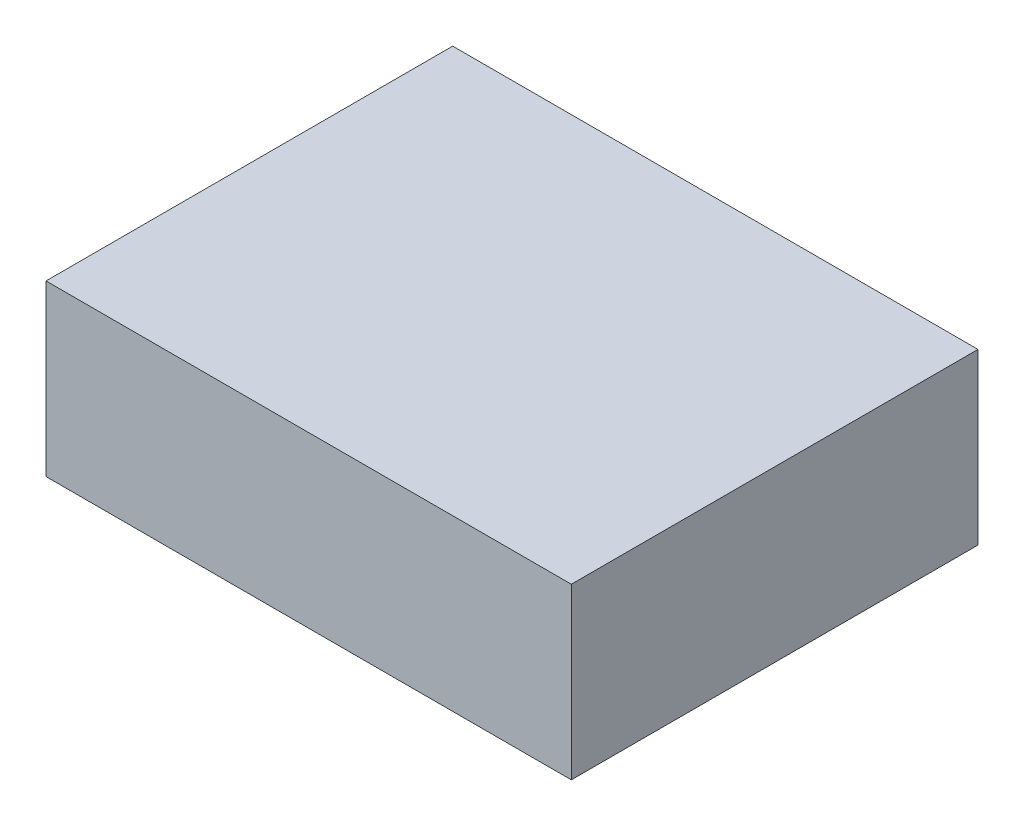
SolidWorks part; units mm, degrees
ref_plane "Front Plane" through (0, 0, 0) normal (0, 0, 1) x (1, 0, 0)
ref_plane "Top Plane" through (0, 0, 0) normal (0, 1, 0) x (1, 0, 0)
ref_plane "Right Plane" through (0, 0, 0) normal (1, 0, 0) x (0, 0, -1)
sketch "Sketch1" plane through (0, 0, 0) normal (0, 1, 0) x (1, 0, 0)
  line L1 (-155, 120) -> (155, 120)
  line L2 (-155, 120) -> (-155, -120)
  line L3 (-155, -120) -> (155, -120)
  line L4 (155, 120) -> (155, -120)
  line L5 (-155, 120) -> (155, -120) construction
  line L6 (-155, -120) -> (155, 120) construction
  point P0 (0, 0)
  dimension "D1" = 310
  dimension "D2" = 240
extrude "Boss-Extrude1" add sketch "Sketch1" along normal blind 100
